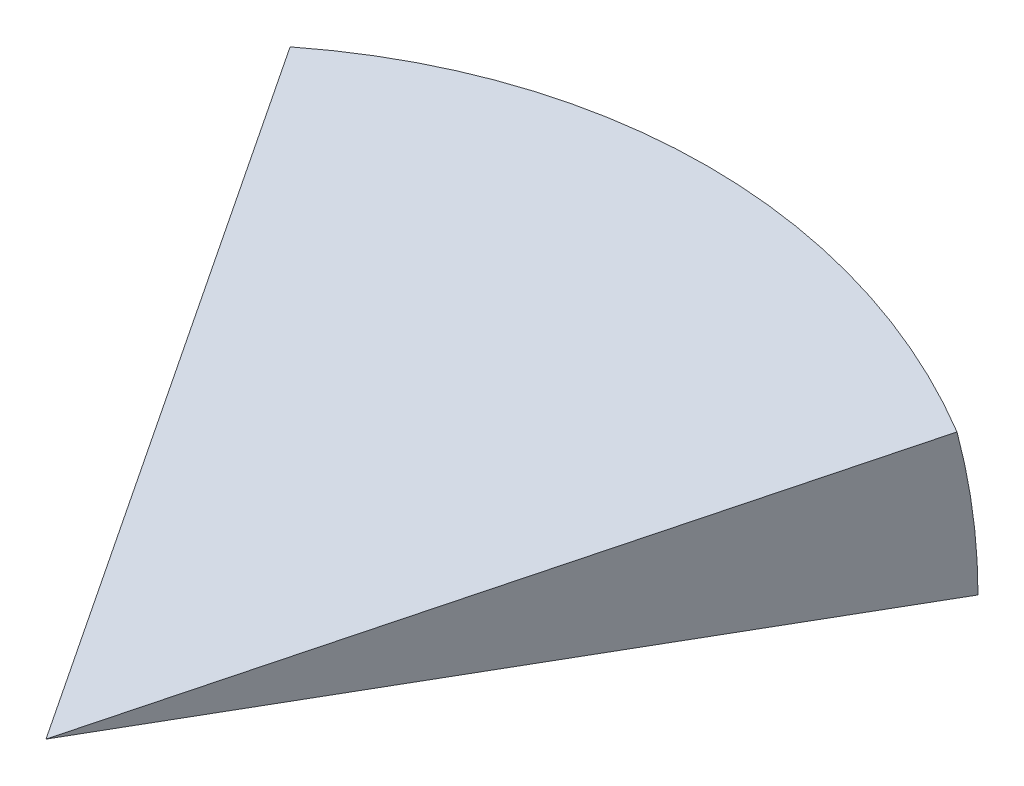
SolidWorks part; units mm, degrees
ref_plane "前视基准面" through (0, 0, 0) normal (0, 0, 1) x (1, 0, 0)
ref_plane "上视基准面" through (0, 0, 0) normal (0, 1, 0) x (1, 0, 0)
ref_plane "右视基准面" through (0, 0, 0) normal (1, 0, 0) x (0, 0, -1)
sketch "草图3" plane through (0, 0, 0) normal (0, 1, 0) x (1, 0, 0)
  line L0 (-30, 0) -> (30, 0)
  arc A0 (-30, 0) -> (30, 0) centre (0, 0) cw
  dimension "D1" = 60
revolve "旋转2" add sketch "草图3" angle 14 about L0
sketch "草图4" plane through (0, 0, 0) normal (0, 0, 1) x (1, 0, 0)
  line L0 (0, 0) -> (0, 14.0611) construction
ref_plane "基准面4" through (0, 0, 0) normal (-0.866, 0, -0.5) x (0, 1, 0)
sketch "草图5" plane through (0, 0, 0) normal (-0.866, 0, -0.5) x (0, 1, 0)
  line L1 (22.3433, 46.9147) -> (-22.3433, 46.9147)
  line L2 (22.3433, 46.9147) -> (22.3433, -46.9147)
  line L3 (22.3433, -46.9147) -> (-22.3433, -46.9147)
  line L4 (-22.3433, 46.9147) -> (-22.3433, -46.9147)
  line L5 (22.3433, 46.9147) -> (-22.3433, -46.9147) construction
  line L6 (22.3433, -46.9147) -> (-22.3433, 46.9147) construction
  point P0 (0, 0)
extrude "切除-拉伸1" cut sketch "草图5" against normal blind 50
ref_plane "基准面5" through (0, 0, 0) normal (-0.866, 0, 0.5) x (0, 1, 0)
sketch "草图6" plane through (0, 0, 0) normal (-0.866, 0, 0.5) x (0, 1, 0)
  line L1 (-12.5445, 38.7669) -> (12.5445, 38.7669)
  line L2 (-12.5445, 38.7669) -> (-12.5445, -38.7669)
  line L3 (-12.5445, -38.7669) -> (12.5445, -38.7669)
  line L4 (12.5445, 38.7669) -> (12.5445, -38.7669)
  line L5 (-12.5445, 38.7669) -> (12.5445, -38.7669) construction
  line L6 (-12.5445, -38.7669) -> (12.5445, 38.7669) construction
  point P0 (0, 0)
extrude "切除-拉伸2" cut sketch "草图6" along normal blind 39
